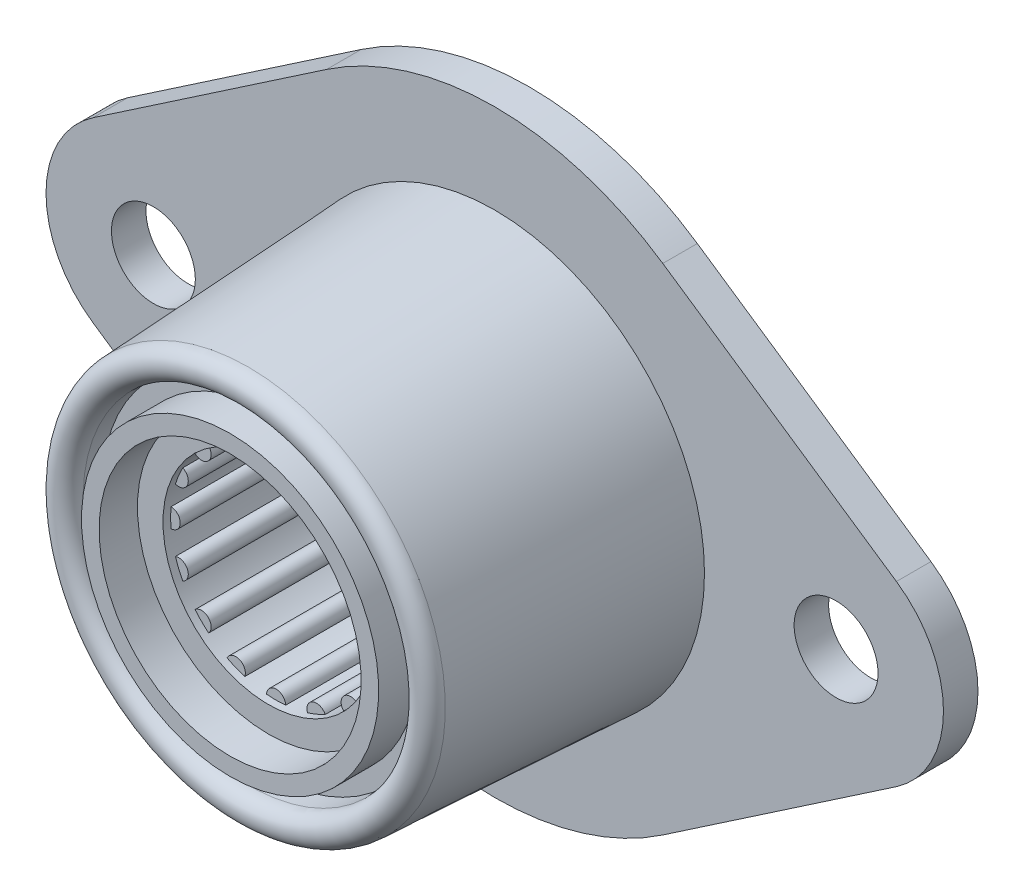
SolidWorks part; units mm, degrees
material "AISI 1020 Steel, Cold Rolled"
ref_plane "Front" through (0, 0, 0) normal (0, 0, 1) x (1, 0, 0)
ref_plane "Top" through (0, 0, 0) normal (0, 1, 0) x (1, 0, 0)
ref_plane "Right" through (0, 0, 0) normal (1, 0, 0) x (0, 0, -1)
sketch "Sketch1" plane through (0, 0, 0) normal (0, 0, 1) x (1, 0, 0)
  line L0 (0, 0) -> (-22.606, 0) construction
  line L1 (0, 0) -> (22.606, 0) construction
  line L2 (-26.6015, 5.8836) -> (-11.1303, 16.39)
  line L3 (11.1303, 16.39) -> (26.6015, 5.8836)
  line L4 (26.6015, -5.8836) -> (11.1303, -16.39)
  line L5 (-11.1303, -16.39) -> (-26.6015, -5.8836)
  arc A0 (11.1303, 16.39) -> (-11.1303, 16.39) centre (0, 0) ccw
  circle A1 centre (-22.606, 0) radius 2.7781
  circle A2 centre (22.606, 0) radius 2.7781
  arc A3 (26.6015, -5.8836) -> (26.6015, 5.8836) centre (22.606, 0) ccw
  arc A4 (-26.6015, 5.8836) -> (-26.6015, -5.8836) centre (-22.606, 0) ccw
  circle A5 centre (0, 0) radius 13.8906
  arc A7 (-11.1303, -16.39) -> (11.1303, -16.39) centre (0, 0) ccw
  dimension "H" = 5.5562
  dimension "C" = 39.624
  dimension "A" = 27.7812
  dimension "B" = 59.436
  dimension "D" = 45.212
extrude "Extrude1" add sketch "Sketch1" along normal blind 2.286
sketch "Sketch2" plane through (0, 0, 0) normal (1, 0, 0) x (0, 0, -1)
  line L0 (0, 13.8906) -> (-2.286, 13.8906)
  line L1 (-2.286, 13.8906) -> (-18.5945, 13.0359)
  line L2 (-18.5413, 11.0039) -> (-17.2713, 11.0039)
  line L3 (-17.2713, 11.0039) -> (-17.2713, 9.8404)
  line L4 (-17.2713, 6.35) -> (0, 6.35)
  line L5 (0, 6.35) -> (0, 13.8906)
  line L6 (-17.2713, 9.8404) -> (-19.812, 9.8404)
  line L7 (-19.812, 9.8404) -> (-19.812, 8.677)
  line L8 (-19.812, 8.677) -> (-17.2713, 8.677)
  line L9 (-17.2713, 9.8404) -> (-17.2713, 8.677) construction
  line L10 (0, 0) -> (-17.2713, 0) construction
  line L11 (-17.2713, 0) -> (-17.2713, 6.35) construction
  line L12 (-17.2713, 7.5135) -> (-17.2713, 6.35)
  line L13 (-17.2713, 8.677) -> (-17.2713, 7.5135)
  line L14 (0, 16.39) -> (0, 19.812) construction
  line L15 (0, 16.39) -> (0, 19.812) construction
  line L16 (-18.5413, 12.0206) -> (-19.558, 12.0206) construction
  arc A0 (-18.5945, 13.0359) -> (-19.558, 12.0206) centre (-18.5413, 12.0206) ccw
  arc A1 (-19.558, 12.0206) -> (-18.5413, 11.0039) centre (-18.5413, 12.0206) ccw
  dimension "F" = 19.558
  dimension "Shaft Dia" = 12.7
  dimension "D3" = 2.032
  dimension "D4" = 1.27
  dimension "D5" = 3
  dimension "G" = 19.812
  dimension "D1" = 19.558
revolve "Revolve1" add sketch "Sketch2" angle 360 about L10
sketch "Sketch3" plane through (0, 0, 17.2713) normal (0, 0, 1) x (1, 0, 0)
  line L0 (0, 0) -> (6.985, 0) construction
  arc A0 (-3.2481, 6.1839) -> (-4.4702, 5.3673) centre (0, 0) ccw
  arc A1 (6.9561, 0.6343) -> (6.9561, -0.6343) centre (6.985, 0) ccw
  circle A2 centre (0, 0) radius 6.35 construction
  arc A3 (6.6694, -2.0759) -> (6.1839, -3.2481) centre (6.4533, -2.673) ccw
  arc A4 (5.3673, -4.4702) -> (4.4702, -5.3673) centre (4.9391, -4.9391) ccw
  arc A5 (3.2481, -6.1839) -> (2.0759, -6.6694) centre (2.673, -6.4533) ccw
  arc A6 (0.6343, -6.9561) -> (-0.6343, -6.9561) centre (0, -6.985) ccw
  arc A7 (-2.0759, -6.6694) -> (-3.2481, -6.1839) centre (-2.673, -6.4533) ccw
  arc A8 (-4.4702, -5.3673) -> (-5.3673, -4.4702) centre (-4.9391, -4.9391) ccw
  arc A9 (-6.1839, -3.2481) -> (-6.6694, -2.0759) centre (-6.4533, -2.673) ccw
  arc A10 (-6.9561, -0.6343) -> (-6.9561, 0.6343) centre (-6.985, 0) ccw
  arc A11 (-6.6694, 2.0759) -> (-6.1839, 3.2481) centre (-6.4533, 2.673) ccw
  arc A12 (-5.3673, 4.4702) -> (-4.4702, 5.3673) centre (-4.9391, 4.9391) ccw
  arc A13 (-3.2481, 6.1839) -> (-2.0759, 6.6694) centre (-2.673, 6.4533) ccw
  arc A14 (-0.6343, 6.9561) -> (0.6343, 6.9561) centre (0, 6.985) ccw
  arc A15 (2.0759, 6.6694) -> (3.2481, 6.1839) centre (2.673, 6.4533) ccw
  arc A16 (4.4702, 5.3673) -> (5.3673, 4.4702) centre (4.9391, 4.9391) ccw
  arc A17 (6.1839, 3.2481) -> (6.6694, 2.0759) centre (6.4533, 2.673) ccw
  arc A18 (-5.3673, 4.4702) -> (-6.1839, 3.2481) centre (0, 0) ccw
  arc A19 (-6.6694, 2.0759) -> (-6.9561, 0.6343) centre (0, 0) ccw
  arc A20 (-6.9561, -0.6343) -> (-6.6694, -2.0759) centre (0, 0) ccw
  arc A21 (-6.1839, -3.2481) -> (-5.3673, -4.4702) centre (0, 0) ccw
  arc A22 (-4.4702, -5.3673) -> (-3.2481, -6.1839) centre (0, 0) ccw
  arc A23 (-2.0759, -6.6694) -> (-0.6343, -6.9561) centre (0, 0) ccw
  arc A24 (0.6343, -6.9561) -> (2.0759, -6.6694) centre (0, 0) ccw
  arc A25 (3.2481, -6.1839) -> (4.4702, -5.3673) centre (0, 0) ccw
  arc A26 (5.3673, -4.4702) -> (6.1839, -3.2481) centre (0, 0) ccw
  arc A27 (6.6694, -2.0759) -> (6.9561, -0.6343) centre (0, 0) ccw
  arc A28 (6.9561, 0.6343) -> (6.6694, 2.0759) centre (0, 0) ccw
  arc A29 (6.1839, 3.2481) -> (5.3673, 4.4702) centre (0, 0) ccw
  arc A30 (4.4702, 5.3673) -> (3.2481, 6.1839) centre (0, 0) ccw
  arc A31 (2.0759, 6.6694) -> (0.6343, 6.9561) centre (0, 0) ccw
  arc A32 (-0.6343, 6.9561) -> (-2.0759, 6.6694) centre (0, 0) ccw
  dimension "D1" = 13.97
extrude "Cut-Extrude2" cut sketch "Sketch3" against normal through all
sketch "Sketch4" plane through (0, 0, 17.2713) normal (0, 0, 1) x (1, 0, 0)
  circle A0 centre (0, 0) radius 6.985
extrude "Cut-Extrude3" cut sketch "Sketch4" against normal blind 0.508
sketch "Sketch5" plane through (0, 0, 0) normal (0, 0, -1) x (-1, 0, 0)
  circle A0 centre (0, 0) radius 6.985
  arc A1 (2.0759, 6.6694) -> (0.6343, 6.9561) centre (0, 0) ccw construction
extrude "Cut-Extrude4" cut sketch "Sketch5" against normal blind 0.508
equation "\"D1@Sketch3\"=\"Shaft Dia@Sketch2\"*1.1"
